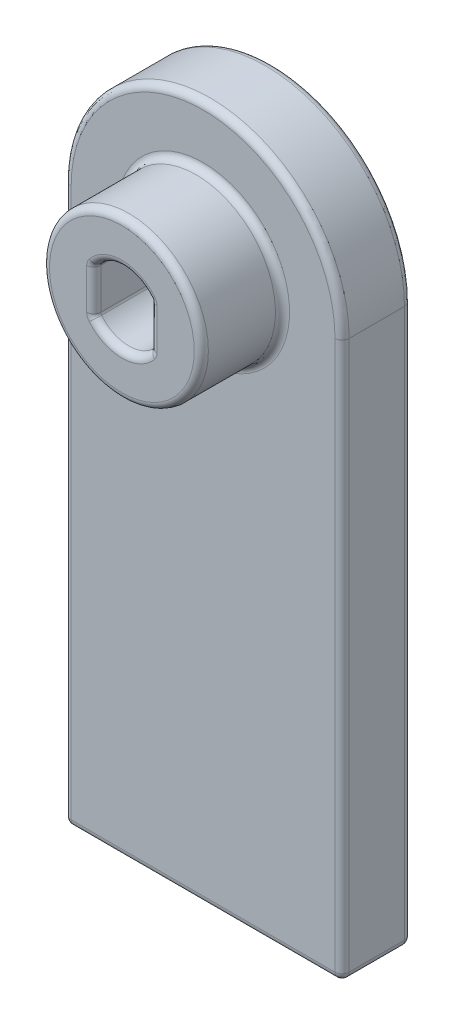
SolidWorks part; units mm, degrees
ref_plane "Front Plane" through (0, 0, 0) normal (0, 0, 1) x (1, 0, 0)
ref_plane "Top Plane" through (0, 0, 0) normal (0, 1, 0) x (1, 0, 0)
ref_plane "Right Plane" through (0, 0, 0) normal (1, 0, 0) x (0, 0, -1)
sketch "Sketch1" plane through (0, 0, 0) normal (0, 0, 1) x (1, 0, 0)
  line L0 (-10, 0) -> (-10, -40)
  line L1 (-10, -40) -> (10, -40)
  line L2 (10, -40) -> (10, 0)
  arc A0 (-10, 0) -> (10, 0) centre (0, 0) cw
  dimension "D1" = 10
  dimension "D2" = 40
extrude "Boss-Extrude1" add sketch "Sketch1" along normal blind 5
sketch "Sketch2" plane through (0, 0, 5) normal (0, 0, 1) x (1, 0, 0)
  line L1 (2.025, 1.4612) -> (2.025, -1.4612)
  line L2 (-2.025, 1.4612) -> (-2.025, -1.4612)
  circle A0 centre (0, 0) radius 5.715
  arc A2 (-1.9669, -1.6229) -> (1.9669, -1.6229) centre (0, 0) ccw
  arc A5 (1.9669, 1.6229) -> (-1.9669, 1.6229) centre (0, 0) ccw
  arc A6 (-2.025, -1.4612) -> (-1.9669, -1.6229) centre (-1.771, -1.4612) ccw
  arc A7 (2.025, -1.4612) -> (1.9669, -1.6229) centre (1.771, -1.4612) cw
  arc A8 (2.025, 1.4612) -> (1.9669, 1.6229) centre (1.771, 1.4612) ccw
  arc A9 (-2.025, 1.4612) -> (-1.9669, 1.6229) centre (-1.771, 1.4612) cw
  dimension "D1" = 11.43
  dimension "D3" = 4.05
  dimension "D4" = 5.1
  dimension "D5" = 0.254
extrude "Boss-Extrude2" add sketch "Sketch2" along normal blind 5.842
sketch "Sketch3" plane through (0, 0, 5) normal (0, 0, 1) x (1, 0, 0)
  line L0 (-2.025, 1.4612) -> (-2.025, -1.4612)
  line L1 (-2.025, 1.4612) -> (-2.025, -1.4612) construction
  line L2 (2.025, 1.4612) -> (2.025, -1.4612)
  arc A0 (-2.025, -1.4612) -> (-1.9669, -1.6229) centre (-1.771, -1.4612) ccw construction
  arc A1 (-1.9669, 1.6229) -> (1.9669, 1.6229) centre (0, 0) cw
  arc A2 (1.9669, 1.6229) -> (-1.9669, 1.6229) centre (0, 0) ccw construction
  arc A3 (2.025, 1.4612) -> (1.9669, 1.6229) centre (1.771, 1.4612) ccw construction
  arc A4 (-1.9669, -1.6229) -> (1.9669, -1.6229) centre (0, 0) ccw
  arc A5 (-1.9669, -1.6229) -> (1.9669, -1.6229) centre (0, 0) ccw construction
  arc A6 (-2.025, 1.4612) -> (-1.9669, 1.6229) centre (-1.771, 1.4612) cw
  arc A7 (-1.9669, 1.6229) -> (-2.025, 1.4612) centre (-1.771, 1.4612) ccw construction
  arc A8 (1.9669, 1.6229) -> (2.025, 1.4612) centre (1.771, 1.4612) cw
  arc A9 (2.025, -1.4612) -> (1.9669, -1.6229) centre (1.771, -1.4612) cw
  arc A10 (1.9669, -1.6229) -> (2.025, -1.4612) centre (1.771, -1.4612) ccw construction
  arc A11 (-1.9669, -1.6229) -> (-2.025, -1.4612) centre (-1.771, -1.4612) cw
extrude "Cut-Extrude1" cut sketch "Sketch3" against normal up to next
fillet "Fillet1" radius 0.508 28 edges at (5.715, 0, 10.842) (-5.715, 0, 5) (10, -20, 5) (-10, -20, 5) (10, -20, 0) (-10, -20, 0) (-2.01, 1.5471, 0) (0, 2.55, 0) (2.01, 1.5471, 0) (2.025, 0, 0) (2.01, -1.5471, 0) (0, -2.55, 0) (-2.01, -1.5471, 0) (2.01, 1.5471, 10.842) (2.025, 0, 10.842) (2.01, -1.5471, 10.842) (0, -2.55, 10.842) (-2.01, -1.5471, 10.842) (-2.025, 0, 10.842) (-2.01, 1.5471, 10.842) (-10, -40, 2.5) (0, -40, 5) (10, -40, 2.5) (0, -40, 0) (0, 10, 5) (0, 10, 0) (-2.025, 0, 0) (0, 2.55, 10.842)
